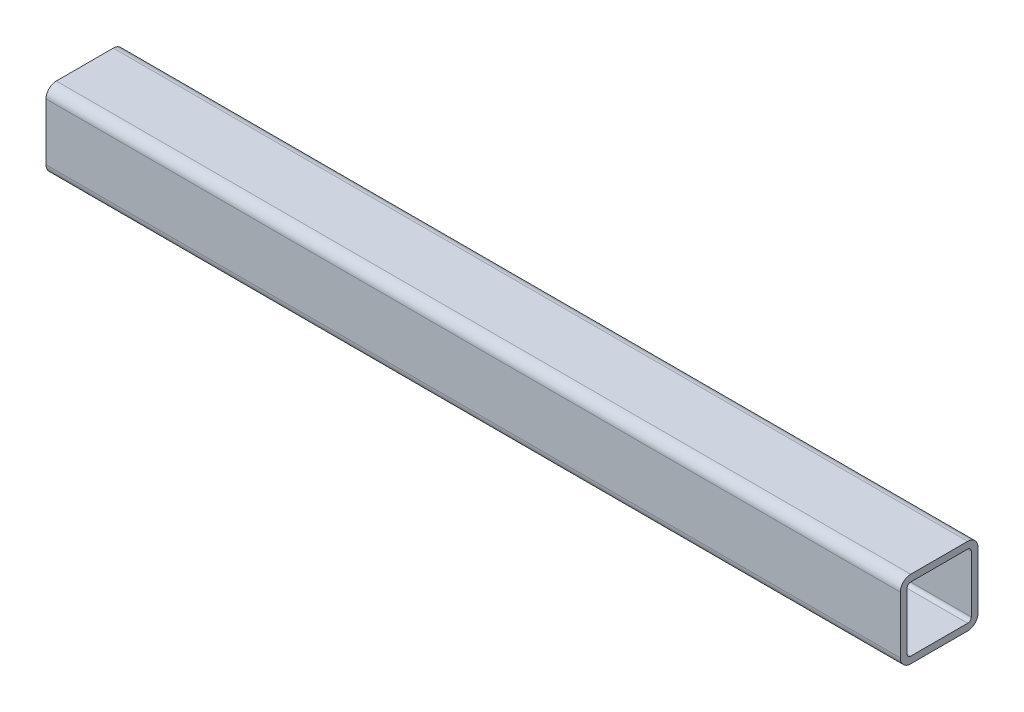
SolidWorks part; units mm, degrees
material "Plain Carbon Steel"
ref_plane "Front Plane" through (0, 0, 0) normal (0, 0, 1) x (1, 0, 0)
ref_plane "Top Plane" through (0, 0, 0) normal (0, 1, 0) x (1, 0, 0)
ref_plane "Right Plane" through (0, 0, 0) normal (1, 0, 0) x (0, 0, -1)
sketch "Sketch1" plane through (0, 0, 0) normal (1, 0, 0) x (0, 0, -1)
  line L0 (0, 2.54) -> (0, 16.51)
  line L1 (-2.54, 19.05) -> (-16.51, 19.05)
  line L2 (-19.05, 16.51) -> (-19.05, 2.54)
  line L3 (-16.51, 0) -> (-2.54, 0)
  line L4 (-1.651, 2.54) -> (-1.651, 16.51)
  line L5 (-2.54, 17.399) -> (-16.51, 17.399)
  line L6 (-17.399, 16.51) -> (-17.399, 2.54)
  line L7 (-16.51, 1.651) -> (-2.54, 1.651)
  arc A0 (-19.05, 2.54) -> (-16.51, 0) centre (-16.51, 2.54) ccw
  arc A1 (0, 2.54) -> (-2.54, 0) centre (-2.54, 2.54) cw
  arc A2 (0, 16.51) -> (-2.54, 19.05) centre (-2.54, 16.51) ccw
  arc A3 (-19.05, 16.51) -> (-16.51, 19.05) centre (-16.51, 16.51) cw
  arc A4 (-1.651, 16.51) -> (-2.54, 17.399) centre (-2.54, 16.51) ccw
  arc A5 (-17.399, 16.51) -> (-16.51, 17.399) centre (-16.51, 16.51) cw
  arc A6 (-17.399, 2.54) -> (-16.51, 1.651) centre (-16.51, 2.54) ccw
  arc A7 (-1.651, 2.54) -> (-2.54, 1.651) centre (-2.54, 2.54) cw
  point P12 (0, 0)
  point P15 (0, 19.05)
  point P18 (-19.05, 19.05)
  dimension "D3" = 2.54
  dimension "D1" = 19.05
  dimension "D2" = 19.05
  dimension "D4" = 1.651
extrude "Boss-Extrude1" add sketch "Sketch1" along normal blind 209.55
